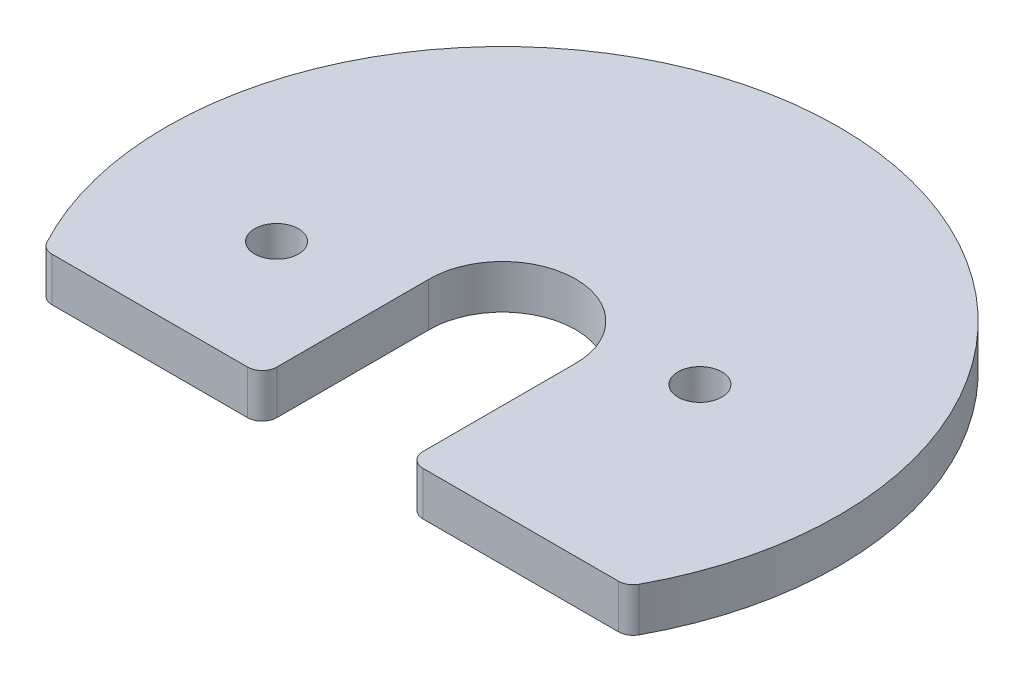
SolidWorks part; units mm, degrees
ref_plane "Front Plane" through (0, 0, 0) normal (0, 0, 1) x (1, 0, 0)
ref_plane "Top Plane" through (0, 0, 0) normal (0, 1, 0) x (1, 0, 0)
ref_plane "Right Plane" through (0, 0, 0) normal (1, 0, 0) x (0, 0, -1)
sketch "Sketch1" plane through (0, 0, 0) normal (0, 1, 0) x (1, 0, 0)
  circle A0 centre (0, 0) radius 23
  dimension "D1" = 46
extrude "Boss-Extrude1" add sketch "Sketch1" along normal blind 3
sketch "Sketch2" plane through (0, 0, 0) normal (0, -1, 0) x (1, 0, 0)
  circle A0 centre (-12.45, 3) radius 1.5
  circle A1 centre (10.5, -3) radius 1.5
extrude "Cut-Extrude1" cut sketch "Sketch2" against normal blind 10
sketch "Sketch3" plane through (0, 3, 0) normal (0, 1, 0) x (1, 0, 0)
  circle A0 centre (0, 0) radius 5
  dimension "D1" = 10
extrude "Cut-Extrude2" cut sketch "Sketch3" against normal blind 10
sketch "Sketch4" plane through (0, 3, 0) normal (0, 1, 0) x (1, 0, 0)
  line L0 (-4.9995, 0.0677) -> (-4.9995, -6.7221)
  line L1 (-5.203, -24.8725) -> (4.797, -24.8725)
  line L2 (4.9995, -11.4325) -> (4.9995, 0.0677)
  line L3 (4.9995, 0.0677) -> (-4.9995, 0.0677)
  line L4 (-4.9995, -11.4325) -> (-4.9995, -6.7221)
  line L6 (-5.203, -24.8725) -> (-23.9492, -24.8725)
  line L8 (-4.9995, -11.4325) -> (-23.9492, -11.4325)
  line L9 (-23.9492, -24.8725) -> (-23.9492, -11.4325)
  line L10 (4.797, -24.8725) -> (29.3168, -24.8725)
  line L12 (4.9995, -11.4325) -> (29.3168, -11.4325)
  line L13 (29.3168, -24.8725) -> (29.3168, -11.4325)
  circle A0 centre (0, 0) radius 5 construction
  dimension "D1" = 13.44
  dimension "D2" = 11.5002
  dimension "D3" = 11.5002
extrude "Cut-Extrude3" cut sketch "Sketch4" against normal blind 10
fillet "Fillet1" radius 1 4 edges at (19.9574, 1.5, 11.4325) (-19.9574, 1.5, 11.4325) (4.9995, 1.5, 11.4325) (-4.9995, 1.5, 11.4325)
